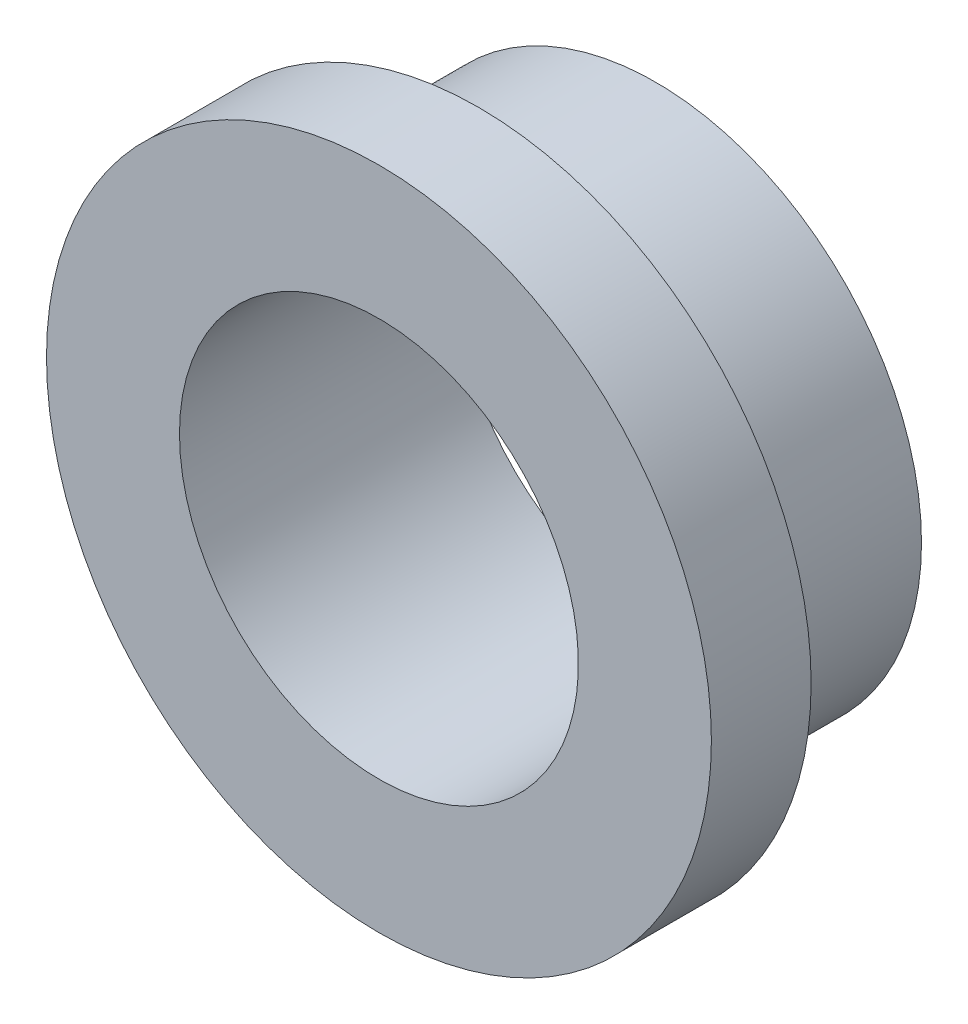
SolidWorks part; units mm, degrees
material "Tin Bearing Bronze"
ref_plane "Front Plane" through (0, 0, 0) normal (0, 0, 1) x (1, 0, 0)
ref_plane "Top Plane" through (0, 0, 0) normal (0, 1, 0) x (1, 0, 0)
ref_plane "Right Plane" through (0, 0, 0) normal (1, 0, 0) x (0, 0, -1)
sketch "Sketch1" plane through (0, 0, 0) normal (1, 0, 0) x (0, 0, -1)
  line L0 (0, 15.875) -> (4.7625, 15.875)
  line L1 (4.7625, 15.875) -> (4.7625, 12.7)
  line L2 (4.7625, 12.7) -> (13.208, 12.7)
  line L3 (13.208, 12.7) -> (13.208, 9.525)
  line L4 (0, 0) -> (-50000, 0) construction
  line L5 (0, 15.875) -> (0, 9.525)
  line L6 (0, 9.525) -> (13.208, 9.525)
  dimension "D1" = 19.05
  dimension "D2" = 25.4
  dimension "D3" = 31.75
  dimension "D4" = 4.7625
  dimension "D5" = 13.208
revolve "Revolve1" add sketch "Sketch1" angle 360 about L4
